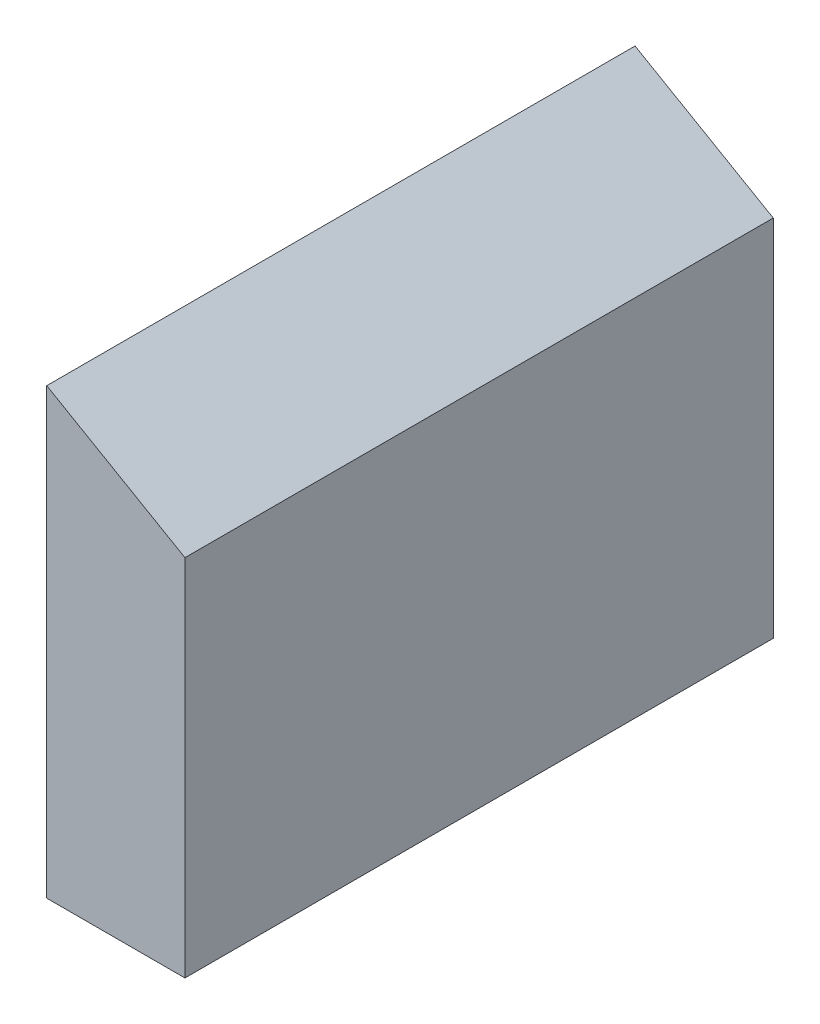
SolidWorks part; units mm, degrees
ref_plane "Front Plane" through (0, 0, 0) normal (0, 0, 1) x (1, 0, 0)
ref_plane "Top Plane" through (0, 0, 0) normal (0, 1, 0) x (1, 0, 0)
ref_plane "Right Plane" through (0, 0, 0) normal (1, 0, 0) x (0, 0, -1)
sketch "Sketch1" plane through (0, 0, 0) normal (0, 0, 1) x (1, 0, 0)
  line L0 (0, 0) -> (10, 0)
  line L1 (0, 0) -> (0, 32.118)
  line L2 (0, 32.118) -> (10, 26.34)
  line L3 (10, 26.34) -> (10, 0)
  dimension "D1" = 10
  dimension "D2" = 32.118
  dimension "D3" = 26.34
extrude "Boss-Extrude1" add sketch "Sketch1" along normal blind 42.57
